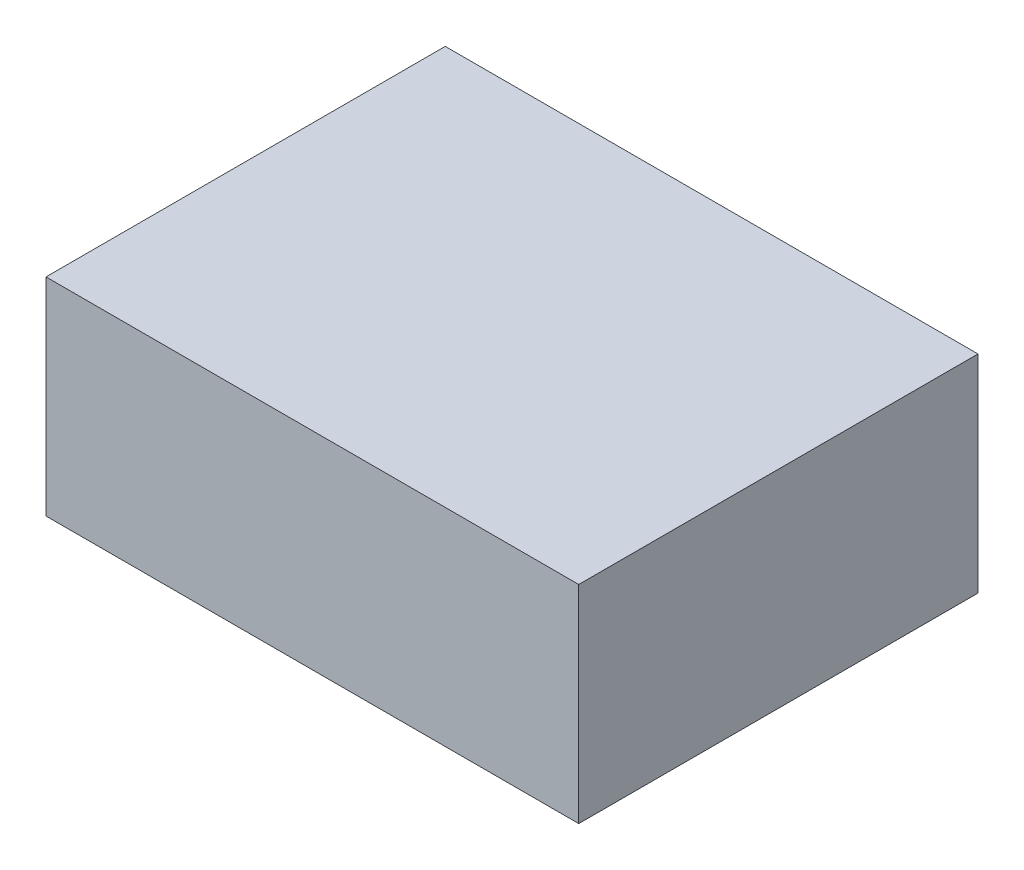
SolidWorks part; units mm, degrees
ref_plane "Front Plane" through (0, 0, 0) normal (0, 0, 1) x (1, 0, 0)
ref_plane "Top Plane" through (0, 0, 0) normal (0, 1, 0) x (1, 0, 0)
ref_plane "Right Plane" through (0, 0, 0) normal (1, 0, 0) x (0, 0, -1)
sketch "Sketch1" plane through (0, 0, 0) normal (0, 0, 1) x (1, 0, 0)
  line L1 (-23.15, -9) -> (23.15, -9)
  line L2 (-23.15, -9) -> (-23.15, 9)
  line L3 (-23.15, 9) -> (23.15, 9)
  line L4 (23.15, -9) -> (23.15, 9)
  line L5 (-23.15, -9) -> (23.15, 9) construction
  line L6 (-23.15, 9) -> (23.15, -9) construction
  point P0 (0, 0)
extrude "Envelope" add sketch "Sketch1" along normal blind 34.7
